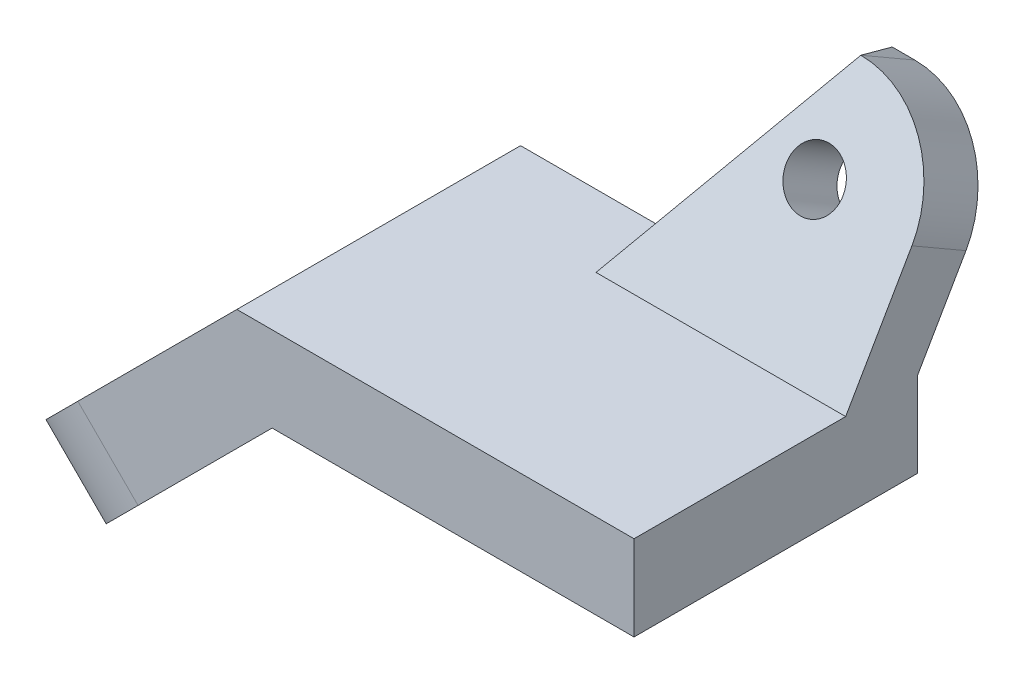
SolidWorks part; units mm, degrees
ref_plane "Front Plane" through (0, 0, 0) normal (0, 0, 1) x (1, 0, 0)
ref_plane "Top Plane" through (0, 0, 0) normal (0, 1, 0) x (1, 0, 0)
ref_plane "Right Plane" through (0, 0, 0) normal (1, 0, 0) x (0, 0, -1)
sketch "Sketch1" plane through (0, 0, 0) normal (0, 0, 1) x (1, 0, 0)
  line L0 (0, 0) -> (70, 0)
  line L1 (0, 0) -> (-45.9619, -45.9619)
  dimension "D1" = 135
  dimension "D2" = 65
  dimension "D3" = 70
extrude "Extrude-Thin1" add sketch "Sketch1" along normal mid plane 50 thin
sketch "Sketch3" plane through (0, 0, 0) normal (-0.7071, 0.7071, 0) x (0, 0, 1)
  line L0 (-25, 0) -> (-25, -65) construction
  line L1 (25, 0) -> (25, -65) construction
  line L2 (-25, -39.6256) -> (-40.6134, -39.6256)
  line L3 (-40.6134, -39.6256) -> (-40.6134, -78.5711)
  line L4 (-40.6134, -78.5711) -> (38.1766, -78.5711)
  line L5 (38.1766, -78.5711) -> (38.1766, -39.6256)
  line L6 (38.1766, -39.6256) -> (25, -39.6256)
  arc A0 (-25, -39.6256) -> (25, -39.6256) centre (0, -39.6256) ccw
extrude "Cut-Extrude1" cut sketch "Sketch3" against normal up to next
sketch "Sketch4" plane through (0, 0, 0) normal (-0.7071, 0.7071, 0) x (0, 0, 1)
  circle A0 centre (0, -39.6256) radius 15
  arc A1 (-25, -39.6256) -> (25, -39.6256) centre (0, -39.6256) ccw construction
  dimension "D1" = 30
extrude "Cut-Extrude2" cut sketch "Sketch4" against normal up to next
sketch "Sketch6" plane through (70, 0, 0) normal (1, 0, 0) x (0, 0, -1)
  line L0 (25, 0) -> (42.5, 30.3109)
  line L1 (25, 0) -> (19.8845, -8.8602)
  line L2 (-25, 0) -> (25, 0) construction
  dimension "D1" = 120
  dimension "D2" = 35
extrude "Extrude-Thin2" add sketch "Sketch6" against normal blind 44 thin thin type one direction wall 11
fillet "Fillet2" radius 18 1 edges at (70, 33.0609, -37.7369)
sketch "Sketch8" plane through (0, -5.3253, -9.2237) normal (0, 0.5, 0.866) x (1, 0, 0)
  line L0 (26, 6.1491) -> (64.7279, 42.2279) construction
  arc A0 (70, 29.5) -> (52, 47.5) centre (52, 29.5) ccw construction
  circle A1 centre (52.2892, 30.6401) radius 5
  dimension "D1" = 10
  dimension "D2" = 17
extrude "Cut-Extrude4" cut sketch "Sketch8" against normal up to next
sketch "Sketch10" plane through (0, -5.3253, -9.2237) normal (0, 0.5, 0.866) x (1, 0, 0)
  line L0 (26, 6.1491) -> (52, 47.5)
  line L1 (52, 47.5) -> (26, 47.5)
  line L2 (26, 47.5) -> (26, 6.1491)
extrude "Cut-Extrude9" cut sketch "Sketch10" along direction (0, 0, -1) on the side against the normal up to surface (12.7017 mm away)
